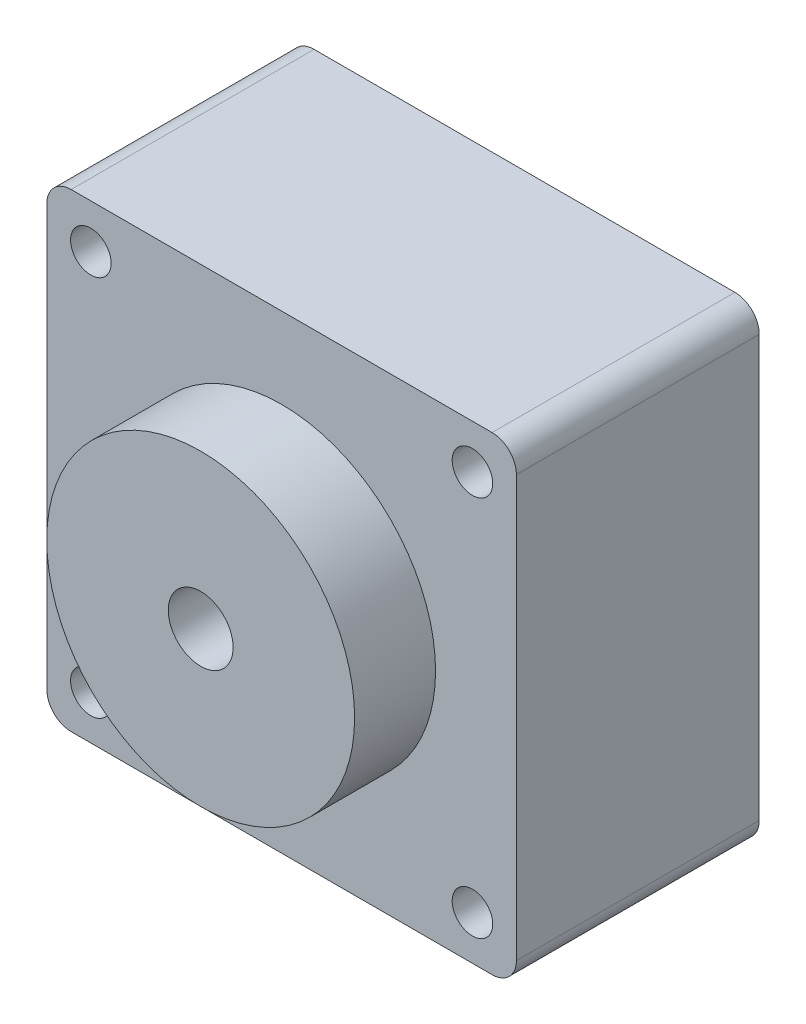
SolidWorks part; units mm, degrees
ref_plane "前视基准面" through (0, 0, 0) normal (0, 0, 1) x (1, 0, 0)
ref_plane "上视基准面" through (0, 0, 0) normal (0, 1, 0) x (1, 0, 0)
ref_plane "右视基准面" through (0, 0, 0) normal (1, 0, 0) x (0, 0, -1)
sketch "草图1" plane through (0, 0, 0) normal (0, 0, 1) x (1, 0, 0)
  line L1 (0, 0) -> (58, 0)
  line L2 (0, 0) -> (0, 58)
  line L3 (0, 58) -> (58, 58)
  line L4 (58, 0) -> (58, 58)
  dimension "D1" = 58
  dimension "D2" = 58
extrude "凸台-拉伸1" add sketch "草图1" along normal blind 30
sketch "草图2" plane through (0, 0, 30) normal (0, 0, 1) x (1, 0, 0)
  line L0 (0, 0) -> (58, 0) construction
  line L1 (0, 58) -> (0, 0) construction
  circle A0 centre (29, 29) radius 19.015
  dimension "D1" = 29
  dimension "D2" = 29
  dimension "D3" = 38.03
extrude "凸台-拉伸2" add sketch "草图2" along normal blind 10
sketch "草图3" plane through (0, 0, 40) normal (0, 0, 1) x (1, 0, 0)
  circle A0 centre (29, 29) radius 4.005
  dimension "D1" = 8.01
extrude "切除-拉伸2" cut sketch "草图3" against normal blind 25
sketch "草图4" plane through (0, 0, 30) normal (0, 0, 1) x (1, 0, 0)
  circle A0 centre (52.57, 52.57) radius 2.505
  circle A2 centre (5.43, 52.57) radius 2.505
  circle A3 centre (5.43, 5.43) radius 2.505
  circle A4 centre (52.57, 5.43) radius 2.505
  dimension "D1" = 5.01
  dimension "D2" = 5.01
  dimension "D3" = 5.01
  dimension "D4" = 5.01
extrude "切除-拉伸3" cut sketch "草图4" against normal through all
fillet "圆角1" radius 3 1 edges at (58, 58, 15)
fillet "圆角2" radius 3 1 edges at (58, 0, 15)
fillet "圆角3" radius 3 1 edges at (0, 58, 15)
fillet "圆角4" radius 3 1 edges at (0, 0, 15)
